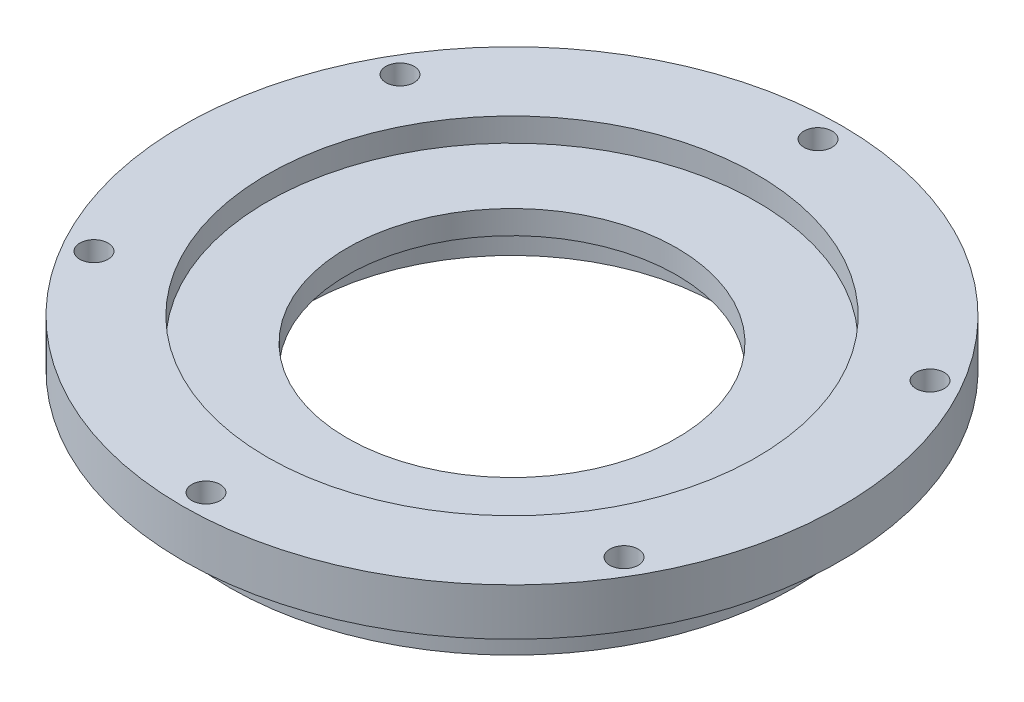
SolidWorks part; units mm, degrees
ref_plane "Front Plane" through (0, 0, 0) normal (0, 0, 1) x (1, 0, 0)
ref_plane "Top Plane" through (0, 0, 0) normal (0, 1, 0) x (1, 0, 0)
ref_plane "Right Plane" through (0, 0, 0) normal (1, 0, 0) x (0, 0, -1)
sketch "Sketch1" plane through (0, 0, 0) normal (0, 1, 0) x (1, 0, 0)
  circle A0 centre (0, 0) radius 35
  circle A1 centre (0, 0) radius 17.5
  dimension "D1" = 70
  dimension "D2" = 35
extrude "Boss-Extrude1" add sketch "Sketch1" along normal blind 5
sketch "Sketch2" plane through (0, 0, 0) normal (0, -1, 0) x (1, 0, 0)
  circle A0 centre (0, 0) radius 30
  circle A1 centre (0, 0) radius 22
  circle A2 centre (0, 27.5) radius 1.6
  circle A3 centre (5.5357, 26.9371) radius 1.6
  circle A4 centre (10.8448, 25.2713) radius 1.6
  circle A5 centre (15.7099, 22.571) radius 1.6
  circle A6 centre (19.9318, 18.9466) radius 1.6
  circle A7 centre (23.3377, 14.5465) radius 1.6
  circle A8 centre (25.7882, 9.5509) radius 1.6
  circle A9 centre (27.1829, 4.1643) radius 1.6
  circle A10 centre (27.4647, -1.3929) radius 1.6
  circle A11 centre (26.6221, -6.8929) radius 1.6
  circle A12 centre (24.6896, -12.1108) radius 1.6
  circle A13 centre (21.7463, -16.8329) radius 1.6
  circle A14 centre (17.9127, -20.8658) radius 1.6
  circle A15 centre (13.3458, -24.0445) radius 1.6
  circle A16 centre (8.2325, -26.2388) radius 1.6
  circle A17 centre (2.7821, -27.3589) radius 1.6
  circle A18 centre (-2.7821, -27.3589) radius 1.6
  circle A19 centre (-8.2325, -26.2388) radius 1.6
  circle A20 centre (-13.3458, -24.0445) radius 1.6
  circle A21 centre (-17.9127, -20.8658) radius 1.6
  circle A22 centre (-21.7463, -16.8329) radius 1.6
  circle A23 centre (-24.6896, -12.1108) radius 1.6
  circle A24 centre (-26.6221, -6.8929) radius 1.6
  circle A25 centre (-27.4647, -1.3929) radius 1.6
  circle A26 centre (-27.1829, 4.1643) radius 1.6
  circle A27 centre (-25.7882, 9.5509) radius 1.6
  circle A28 centre (-23.3377, 14.5465) radius 1.6
  circle A29 centre (-19.9318, 18.9466) radius 1.6
  circle A30 centre (-15.7099, 22.571) radius 1.6
  circle A31 centre (-10.8448, 25.2713) radius 1.6
  circle A32 centre (-5.5357, 26.9371) radius 1.6
  point P68 (0, 0)
  dimension "D1" = 60
  dimension "D2" = 44
  dimension "D3" = 3.2
  dimension "D4" = 27.5
  dimension "D5" = 31
extrude "Boss-Extrude2" add sketch "Sketch2" along normal blind 5
sketch "Sketch3" plane through (0, 5, 0) normal (0, 1, 0) x (1, 0, 0)
  circle A0 centre (0, 32.5) radius 1.5
  circle A1 centre (28.1458, 16.25) radius 1.5
  circle A2 centre (28.1458, -16.25) radius 1.5
  circle A3 centre (0, -32.5) radius 1.5
  circle A4 centre (-28.1458, -16.25) radius 1.5
  circle A5 centre (-28.1458, 16.25) radius 1.5
  point P15 (0, 0)
  dimension "D1" = 3
  dimension "D2" = 32.5
  dimension "D3" = 6
extrude "Cut-Extrude1" cut sketch "Sketch3" against normal blind 5
sketch "Sketch4" plane through (0, 5, 0) normal (0, 1, 0) x (1, 0, 0)
  circle A0 centre (0, 0) radius 26
  dimension "D1" = 52
extrude "Cut-Extrude2" cut sketch "Sketch4" against normal blind 2.5
